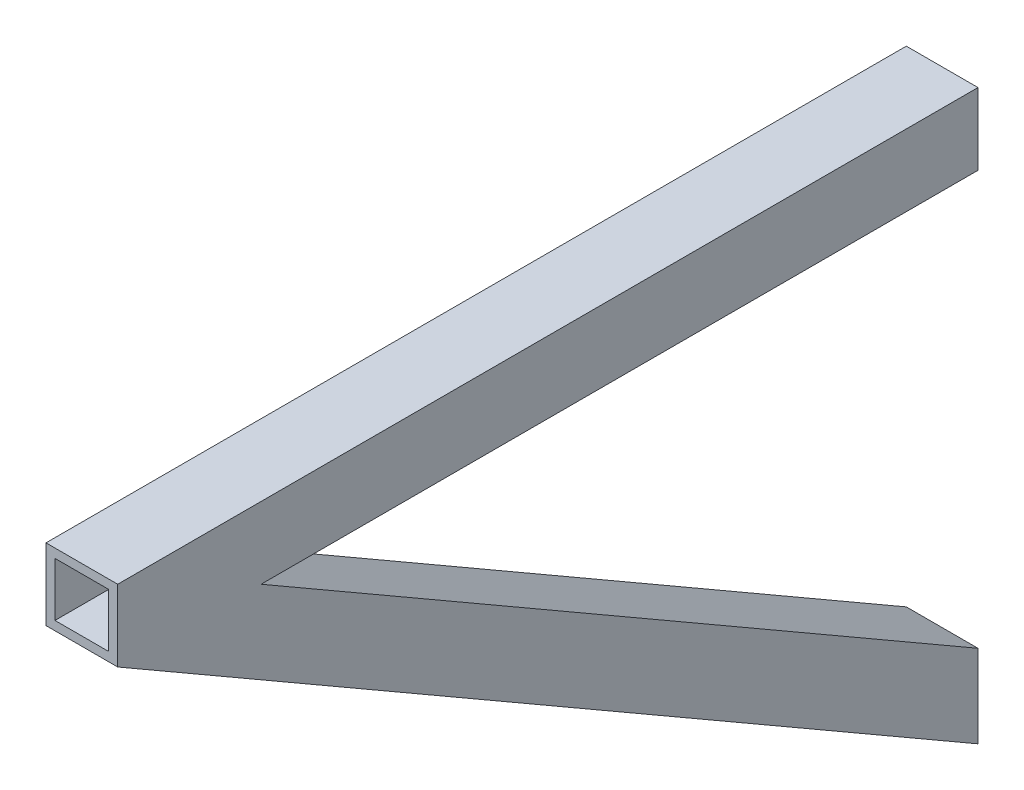
SolidWorks part; units mm, degrees
ref_plane "Front Plane" through (0, 0, 0) normal (0, 0, 1) x (1, 0, 0)
ref_plane "Top Plane" through (0, 0, 0) normal (0, 1, 0) x (1, 0, 0)
ref_plane "Right Plane" through (0, 0, 0) normal (1, 0, 0) x (0, 0, -1)
sketch "Sketch1" plane through (0, 0, 0) normal (0, 0, 1) x (1, 0, 0)
  line L1 (0, 0) -> (25.4, 0)
  line L2 (0, 0) -> (0, 25.4)
  line L3 (0, 25.4) -> (25.4, 25.4)
  line L4 (25.4, 0) -> (25.4, 25.4)
  line L5 (3.175, 22.225) -> (22.225, 22.225)
  line L6 (3.175, 22.225) -> (3.175, 3.175)
  line L7 (3.175, 3.175) -> (22.225, 3.175)
  line L8 (22.225, 22.225) -> (22.225, 3.175)
  dimension "D1" = 25.4
  dimension "D2" = 25.4
  dimension "D3" = 3.175
  dimension "D4" = 3.175
  dimension "D5" = 3.175
  dimension "D6" = 3.175
extrude "Boss-Extrude1" add sketch "Sketch1" along normal blind 304.8
sketch "Sketch2" plane through (0, 0, 0) normal (0, -1, 0) x (1, 0, 0)
  line L0 (0, 304.8) -> (0, 0) construction
  line L1 (25.4, 304.8) -> (0, 304.8)
  line L2 (25.4, 304.8) -> (25.4, 254)
  line L3 (25.4, 254) -> (0, 254)
  line L4 (0, 304.8) -> (0, 254)
  line L6 (22.225, 298.45) -> (3.175, 298.45)
  line L7 (22.225, 298.45) -> (22.225, 260.35)
  line L8 (22.225, 260.35) -> (3.175, 260.35)
  line L9 (3.175, 298.45) -> (3.175, 260.35)
  dimension "D1" = 50.8
  dimension "D2" = 3.175
  dimension "D3" = 6.35
  dimension "D4" = 3.175
  dimension "D5" = 6.35
sketch "Sketch3" plane through (25.4, 0, 0) normal (1, 0, 0) x (0, 0, -1)
  line L0 (-279.4, 0) -> (50.5557, -190.5)
  line L1 (-304.8, 0) -> (-254, 0) construction
  line L2 (-304.8, 0) -> (0, 0) construction
  dimension "D1" = 30
  dimension "D2" = 381
sweep "Sweep1" add profiles "Sketch2" path "Sketch3"
sketch "Sketch4" plane through (0, 25.4, 0) normal (0, 1, 0) x (1, 0, 0)
  line L1 (0, 0) -> (26.6901, 0)
  line L2 (0, 0) -> (0, 109.7928)
  line L3 (0, 109.7928) -> (26.6901, 109.7928)
  line L4 (26.6901, 0) -> (26.6901, 109.7928)
extrude "Cut-Extrude1" cut sketch "Sketch4" against normal through all
